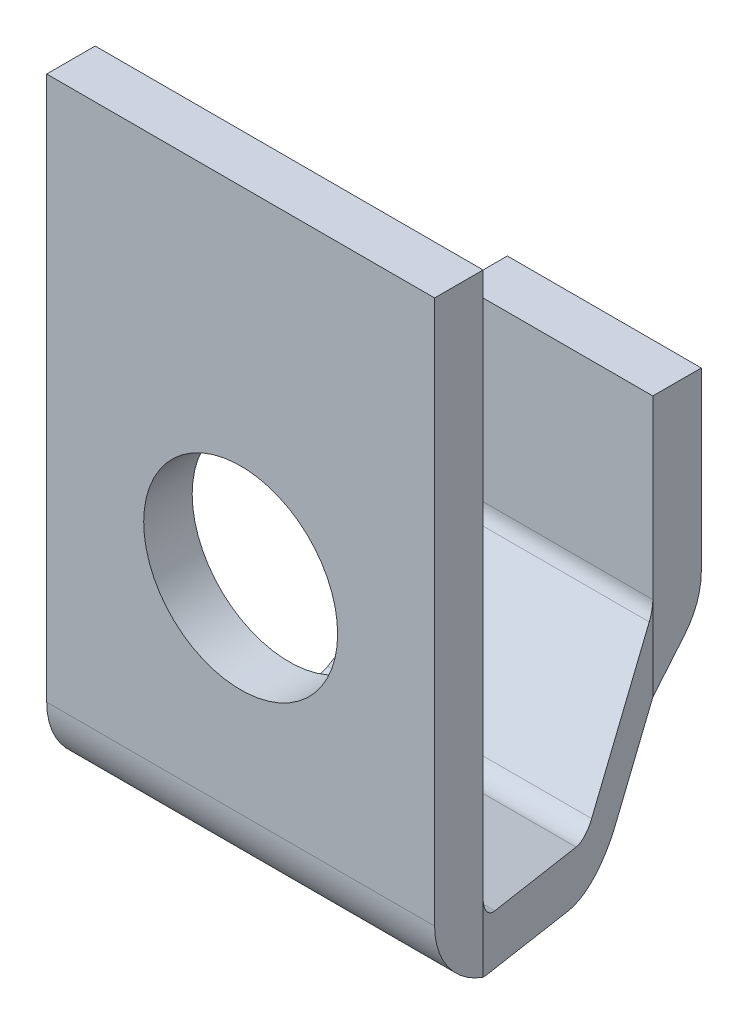
SolidWorks part; units mm, degrees
ref_plane "Front Plane" through (0, 0, 0) normal (0, 0, 1) x (1, 0, 0)
ref_plane "Top Plane" through (0, 0, 0) normal (0, 1, 0) x (1, 0, 0)
ref_plane "Right Plane" through (0, 0, 0) normal (1, 0, 0) x (0, 0, -1)
sketch "Sketch1" plane through (0, 0, 0) normal (0, 1, 0) x (1, 0, 0)
  line L1 (-2, -0.25) -> (2, -0.25)
  line L2 (-2, -0.25) -> (-2, 0.25)
  line L3 (-2, 0.25) -> (2, 0.25)
  line L4 (2, -0.25) -> (2, 0.25)
  line L5 (-2, -0.25) -> (2, 0.25) construction
  line L6 (-2, 0.25) -> (2, -0.25) construction
  point P0 (0, 0)
  dimension "D1" = 4
  dimension "D2" = 0.5
sketch "Sketch2" plane through (0, 0, 0) normal (1, 0, 0) x (0, 0, -1)
  line L0 (0, 0) -> (0, -5.6096)
  line L1 (0.3787, -6.0947) -> (1.6955, -6.4239)
  line L2 (2.2009, -6.2589) -> (3.1341, -5.1391)
  line L3 (3.25, -4.819) -> (3.25, -3)
  arc A0 (3.1341, -5.1391) -> (3.25, -4.819) centre (2.75, -4.819) ccw
  arc A1 (1.6955, -6.4239) -> (2.2009, -6.2589) centre (1.8168, -5.9388) ccw
  arc A2 (0, -5.6096) -> (0.3787, -6.0947) centre (0.5, -5.6096) ccw
  point P8 (3.25, -5)
  point P11 (2, -6.5)
  point P14 (0, -6)
  dimension "D7" = 0.5
  dimension "D1" = 6
  dimension "D2" = 3.25
  dimension "D3" = 2
  dimension "D4" = 0.5
  dimension "D5" = 1.5
  dimension "D6" = 2
sweep "Sweep1" add profiles "Sketch1" path "Sketch2"
sketch "Sketch6" plane through (0, 0, 0) normal (0, 1, 0) x (1, 0, 0)
  line L0 (2, -0.25) -> (-2, -0.25)
  line L1 (-2, -0.25) -> (-2, 0.25)
  line L2 (-2, 0.25) -> (-1, 3)
  line L3 (2, 3) -> (-2, 3) construction
  line L4 (-1, 3) -> (-1, 3.5)
  line L5 (-2, 3.5) -> (2, 3.5) construction
  line L6 (-1, 3.5) -> (1, 3.5)
  line L7 (1, 3.5) -> (1, 3)
  line L8 (1, 3) -> (2, 0.25)
  line L9 (2, 0.25) -> (2, -0.25)
  dimension "D1" = 2
  dimension "D2" = 1
extrude "Cut-Extrude1" cut sketch "Sketch6" against normal through all flip side to cut
sketch "Sketch7" plane through (0, 0, 0.25) normal (0, 0, 1) x (1, 0, 0)
  line L0 (-2, 0) -> (2, 0) construction
  circle A0 centre (0, -3.5) radius 1
  dimension "D1" = 3.5
extrude "Cut-Extrude2" cut sketch "Sketch7" against normal blind 0.5
